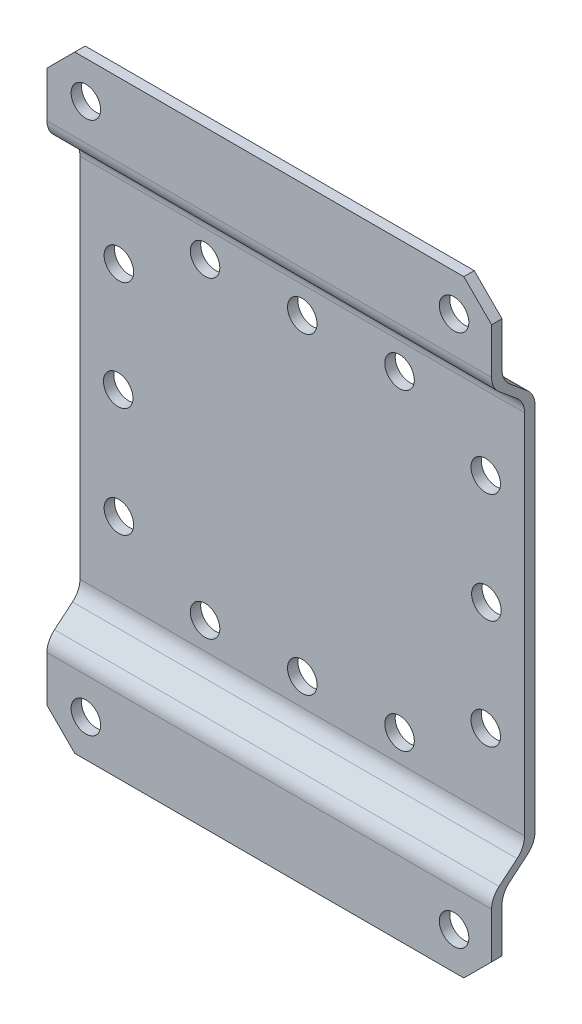
SolidWorks part; units mm, degrees
ref_plane "前视基准面" through (0, 0, 0) normal (0, 0, 1) x (1, 0, 0)
ref_plane "上视基准面" through (0, 0, 0) normal (0, 1, 0) x (1, 0, 0)
ref_plane "右视基准面" through (0, 0, 0) normal (1, 0, 0) x (0, 0, -1)
sketch "草图1" plane through (0, 0, 0) normal (1, 0, 0) x (0, 0, -1)
  line L0 (-40.5105, 0) -> (45.4932, 0) construction
  line L1 (0, -28.5199) -> (0, 87.4342) construction
  line L2 (0, 87.4342) -> (3, 87.4342)
  line L3 (3, 87.4342) -> (3, 66.7405)
  line L4 (5.1539, 62.1353) -> (10.3461, 57.7989)
  line L5 (12.5, 53.1937) -> (12.5, -53.1937)
  line L6 (0, 87.4342) -> (0, 66.2853)
  line L7 (2.1539, 61.6801) -> (7.3461, 57.3437)
  line L8 (9.5, 52.7385) -> (9.5, -52.7385)
  line L9 (0, 28.5199) -> (0, -87.4342) construction
  line L10 (2.1539, -61.6801) -> (7.3461, -57.3437)
  line L11 (0, -87.4342) -> (0, -66.2853)
  line L12 (5.1539, -62.1353) -> (10.3461, -57.7989)
  line L13 (3, -87.4342) -> (3, -66.7405)
  line L14 (0, -87.4342) -> (3, -87.4342)
  arc A0 (0, 66.2853) -> (2.1539, 61.6801) centre (6, 66.2853) ccw
  arc A1 (12.5, 53.1937) -> (10.3461, 57.7989) centre (6.5, 53.1937) ccw
  arc A2 (9.5, 52.7385) -> (7.3461, 57.3437) centre (3.5, 52.7385) ccw
  arc A3 (5.1539, 62.1353) -> (3, 66.7405) centre (9, 66.7405) cw
  arc A4 (5.1539, -62.1353) -> (3, -66.7405) centre (9, -66.7405) ccw
  arc A5 (9.5, -52.7385) -> (7.3461, -57.3437) centre (3.5, -52.7385) cw
  arc A6 (12.5, -53.1937) -> (10.3461, -57.7989) centre (6.5, -53.1937) cw
  arc A7 (0, -66.2853) -> (2.1539, -61.6801) centre (6, -66.2853) cw
  point P13 (12.5, 0)
  point P14 (0, 63.479)
  point P18 (12.5, 56)
  point P23 (3, 63.9342)
  point P38 (9.5, 0)
  point P39 (3, -63.9342)
  point P40 (12.5, -56)
  point P41 (0, -63.479)
  dimension "D4" = 6
  dimension "D5" = 6
  dimension "D6" = 6
  dimension "D1" = 3
  dimension "D2" = 23.5
  dimension "D3" = 56
  dimension "D7" = 12.5
  dimension "D8" = 9.5
extrude "凸台-拉伸1" add sketch "草图1" along normal mid plane 128
chamfer "倒角1" distance 8 angle 45 4 edges at (64, 87.4342, -1.5) (64, -87.4342, -1.5) (-64, -87.4342, -1.5) (-64, 87.4342, -1.5)
sketch "草图4" plane through (0, 0, 0) normal (0, 0, 1) x (1, 0, 0)
  line L0 (-80.232, 0) -> (92.2826, 0) construction
  line L1 (0, 0) -> (0, 84.8302) construction
  circle A0 centre (-52.8009, 76.7436) radius 4.25
  circle A1 centre (53.1991, 76.7436) radius 4.25
  circle A2 centre (-52.8009, 31.5) radius 4.25
  circle A4 centre (-28, 45) radius 4.25
  circle A5 centre (0, 45) radius 4.25
  circle A6 centre (52.8009, 31.5) radius 4.25
  circle A7 centre (28, 45) radius 4.25
  circle A8 centre (53.1991, -76.7436) radius 4.25
  circle A9 centre (52.8009, -31.5) radius 4.25
  circle A10 centre (28, -45) radius 4.25
  circle A11 centre (0, -45) radius 4.25
  circle A12 centre (-28, -45) radius 4.25
  circle A13 centre (-52.8009, -31.5) radius 4.25
  circle A14 centre (-52.8009, -76.7436) radius 4.25
  dimension "D1" = 8.5
  dimension "D2" = 106
  dimension "D4" = 45
  dimension "D5" = 8.5
  dimension "D6" = 28
  dimension "D7" = 8.5
  dimension "D8" = 8.5
  dimension "D3" = 31.5
extrude "切除-拉伸1" cut sketch "草图4" against normal through all
sketch "草图6" plane through (0, 0, -12.5) normal (0, 0, -1) x (-1, 0, 0)
  line L0 (-64, -53.1937) -> (-64, 53.1937) construction
  line L1 (0, 6.875) -> (0, -6.875) construction
  circle A0 centre (-53, 0) radius 4.25
  circle A1 centre (-52.8009, 31.5) radius 4.25 construction
  circle A2 centre (53, 0) radius 4.25
  dimension "D1" = 31.5
  dimension "D2" = 11
extrude "切除-拉伸2" cut sketch "草图6" against normal blind 10
